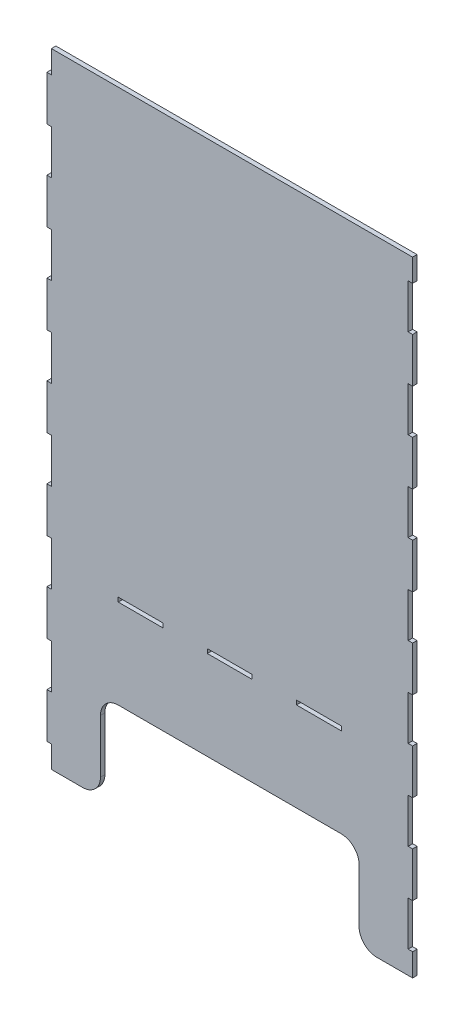
SolidWorks part; units mm, degrees
ref_plane "Ebene vorne" through (0, 0, 0) normal (0, 0, 1) x (1, 0, 0)
ref_plane "Ebene oben" through (0, 0, 0) normal (0, 1, 0) x (1, 0, 0)
ref_plane "Ebene rechts" through (0, 0, 0) normal (1, 0, 0) x (0, 0, -1)
sketch "Skizze1" plane through (0, 0, 0) normal (0, 0, 1) x (1, 0, 0)
  line L0 (0, 0) -> (0, 700)
  line L1 (0, 700) -> (410, 700)
  line L2 (410, 700) -> (410, 0)
  line L3 (410, 0) -> (370, 0)
  line L4 (0, 100) -> (410, 100) construction
  line L5 (60, 20) -> (60, 80)
  line L6 (350, 20) -> (350, 80)
  line L7 (330, 100) -> (80, 100)
  line L8 (40, 0) -> (0, 0)
  arc A0 (80, 100) -> (60, 80) centre (80, 80) ccw
  arc A1 (330, 100) -> (350, 80) centre (330, 80) cw
  arc A2 (40, 0) -> (60, 20) centre (40, 20) ccw
  arc A3 (370, 0) -> (350, 20) centre (370, 20) cw
  point P13 (60, 100)
  point P16 (350, 100)
  point P19 (60, 0)
  point P22 (350, 0)
  dimension "D4" = 20
  dimension "D5" = 20
  dimension "D8" = 20
  dimension "D9" = 20
  dimension "D1" = 700
  dimension "D2" = 410
  dimension "D3" = 100
  dimension "D6" = 60
  dimension "D7" = 60
extrude "Aufsatz-Linear austragen1" add sketch "Skizze1" along normal blind 5 contours L0 L1 L2 L3 A3 L6 A1 L7 A0 L5 A2 L8
sketch "Skizze2" plane through (0, 0, 5) normal (0, 0, 1) x (1, 0, 0)
  line L0 (0, 0) -> (0, 700) construction
  line L1 (79.95, 204.8) -> (130.25, 204.8)
  line L2 (79.95, 204.8) -> (79.95, 200)
  line L3 (79.95, 200) -> (130.25, 200)
  line L4 (130.25, 204.8) -> (130.25, 200)
  point P8 (13.0057, 298.352)
  dimension "D1" = 50.3
  dimension "D2" = 4.8
  dimension "D3" = 79.95
  dimension "D4" = 200
extrude "Schnitt-Linear austragen1" cut sketch "Skizze2" against normal blind 5
pattern_linear "Lineares Muster1" count 3 spacing 99.9 along (1, 0, 0) of "Schnitt-Linear austragen1"
sketch "Skizze3" plane through (0, 0, 5) normal (0, 0, 1) x (1, 0, 0)
  line L0 (0, 700) -> (410, 700) construction
  line L1 (-87.9124, 674.5) -> (5, 674.5)
  line L2 (-87.9124, 674.5) -> (-87.9124, 724.1)
  line L3 (-87.9124, 724.1) -> (5, 724.1)
  line L4 (5, 674.5) -> (5, 724.1)
  dimension "D1" = 49.6
  dimension "D2" = 5
  dimension "D3" = 24.1
extrude "Schnitt-Linear austragen2" cut sketch "Skizze3" against normal blind 5
pattern_linear "Lineares Muster2" count 8 spacing 99.9 along (0, -1, 0) of "Schnitt-Linear austragen2"
ref_plane "Ebene1" through (205, 0, 0) normal (1, 0, 0) x (0, 0, -1)
mirror "Spiegeln2" [suppressed] about plane through (205, 0, 0) normal (1, 0, 0)
sketch "Skizze5" [suppressed] plane through (0, 0, 5) normal (0, 0, 1) x (1, 0, 0)
  line L1 (5, 50.3) -> (-32.3107, 50.3)
  line L2 (5, 50.3) -> (5, -36.4204)
  line L3 (5, -36.4204) -> (-32.3107, -36.4204)
  line L4 (-32.3107, 50.3) -> (-32.3107, -36.4204)
extrude "Schnitt-Linear austragen3" [suppressed] cut sketch "Skizze5" against normal blind 5
sketch "Skizze4" plane through (0, 0, 5) normal (0, 0, 1) x (1, 0, 0)
  line L1 (405, 674.5) -> (491.468, 674.5)
  line L2 (405, 674.5) -> (405, 624.9)
  line L3 (405, 624.9) -> (491.468, 624.9)
  line L4 (491.468, 674.5) -> (491.468, 624.9)
  line L5 (410, 700) -> (410, 0) construction
  dimension "D1" = 49.6
  dimension "D2" = 5
  dimension "D3" = 25.5
extrude "Schnitt-Linear austragen4" cut sketch "Skizze4" against normal blind 5
pattern_linear "Lineares Muster3" count 7 spacing 99.9 along (0, -1, 0) of "Schnitt-Linear austragen4"
sketch "Skizze6" [suppressed] plane through (0, 0, 5) normal (0, 0, 1) x (1, 0, 0)
  line L14 (130.25, -5) -> (130.25, 0)
  line L15 (130.25, 0) -> (79.95, 0)
  line L16 (79.95, 0) -> (79.95, -5)
  line L17 (79.95, -5) -> (130.25, -5)
  line L18 (230.15, -5) -> (230.15, 0)
  line L19 (230.15, 0) -> (179.85, 0)
  line L20 (179.85, 0) -> (179.85, -5)
  line L21 (179.85, -5) -> (230.15, -5)
  line L22 (330.05, -5) -> (330.05, 0)
  line L23 (330.05, 0) -> (279.75, 0)
  line L24 (279.75, 0) -> (279.75, -5)
  line L25 (279.75, -5) -> (330.05, -5)
  line L26 (405, 0) -> (405, -5)
  line L27 (5, 0) -> (5, -5)
  point P16 (0, 0)
sketch "Skizze8" plane through (0, 0, 5) normal (0, 0, 1) x (1, 0, 0)
  line L0 (336.9108, 311.7971) -> (336.9108, 326.3757)
  line L1 (328.6083, 313.8519) -> (328.6083, 327.2541)
  line L2 (328.6083, 333.6697) -> (328.6083, 343.167)
  line L3 (336.9108, 332.9761) -> (336.9108, 342.6373)
  line L4 (327.3926, 291.1393) -> (324.9309, 261.8997)
  line L5 (336.9108, 292.9614) -> (336.9108, 262.1213)
  line L6 (361.3498, 305.4845) -> (370.8351, 305.9572)
  line L7 (340.5076, 297.1544) -> (354.5447, 297.1544)
  line L8 (319.162, 305.9572) -> (306.9363, 311.3902)
  line L9 (319.162, 298.8014) -> (305.6301, 298.0451)
  line L10 (301.0772, 313.9939) -> (292.4018, 317.8492)
  line L11 (299.1984, 297.6857) -> (289.6925, 297.1544)
  line L12 (361.0653, 297.1544) -> (370.6564, 297.1544)
  line L13 (341.558, 304.4982) -> (354.9423, 305.1652)
  line L14 (354.9423, 305.1652) -> (354.4332, 305.5514)
  line L15 (88.2286, 278.6972) -> (88.2286, 273.2138)
  line L16 (102.4933, 343.167) -> (102.4933, 259.9015) construction
  line L17 (116.7579, 273.2138) -> (116.7579, 278.6972)
  line L18 (116.7579, 288.6972) -> (116.7579, 273.2138)
  line L19 (77.4933, 288.6972) -> (78.2286, 288.6972)
  line L20 (126.7579, 288.6972) -> (127.4933, 288.6972)
  line L21 (119.7579, 273.2138) -> (119.7579, 278.6972)
  line L22 (126.7579, 285.6972) -> (127.4933, 285.6972)
  line L23 (77.4933, 285.6972) -> (78.2286, 285.6972)
  line L24 (85.2286, 278.6972) -> (85.2286, 273.2138)
  line L25 (126.7579, 273.2138) -> (126.7579, 278.6972)
  line L26 (126.7579, 282.6972) -> (127.4933, 282.6972)
  line L27 (122.7579, 273.2138) -> (122.7579, 278.6972)
  line L28 (82.2286, 278.6972) -> (82.2286, 273.2138)
  line L29 (77.4933, 282.6972) -> (78.2286, 282.6972)
  line L30 (126.7579, 278.6972) -> (127.4933, 278.6972)
  line L31 (102.4933, 290.7717) -> (102.4933, 229.2493) construction
  line L32 (102.4933, 229.2493) -> (102.4933, 290.7717)
  line L33 (77.4933, 278.6972) -> (78.2286, 278.6972)
  line L34 (78.2286, 278.6972) -> (78.2286, 273.2138)
  line L36 (129.7579, 273.2138) -> (129.7579, 275.8402)
  line L37 (129.7579, 275.8402) -> (129.7579, 275.8402)
  line L38 (75.2286, 275.8402) -> (75.2286, 275.8402)
  line L39 (75.2286, 275.8402) -> (75.2286, 273.2138)
  arc A0 (328.6083, 343.167) -> (292.4018, 317.8492) centre (330.1744, 302.3793) ccw
  arc A1 (328.6083, 333.6697) -> (301.0772, 313.9939) centre (330.1744, 302.3793) ccw
  arc A2 (328.6083, 327.2541) -> (306.9363, 311.3902) centre (330.1744, 302.3793) ccw
  arc A3 (328.6083, 313.8519) -> (319.162, 305.9572) centre (330.1744, 302.3793) ccw
  arc A4 (319.162, 298.8014) -> (340.5076, 297.1544) centre (330.1744, 302.3793) ccw
  arc A5 (305.6301, 298.0451) -> (354.5447, 297.1544) centre (330.1744, 302.3793) ccw
  arc A6 (299.1984, 297.6857) -> (361.0653, 297.1544) centre (330.1744, 302.3793) ccw
  arc A7 (289.6925, 297.1544) -> (370.6564, 297.1544) centre (330.1744, 302.3793) ccw
  arc A8 (341.558, 304.4982) -> (336.9108, 311.7971) centre (330.1744, 302.3793) ccw
  arc A9 (354.9423, 305.1652) -> (336.9108, 326.3757) centre (330.1744, 302.3793) ccw
  arc A10 (361.3498, 305.4845) -> (336.9108, 332.9761) centre (330.1744, 302.3793) ccw
  arc A11 (370.8351, 305.9572) -> (336.9108, 342.6373) centre (330.1744, 302.3793) ccw
  arc A12 (72.5271, 294.2784) -> (132.4594, 294.2784) centre (102.4933, 290.7717) cw
  arc A13 (132.4594, 294.2784) -> (127.4933, 288.6972) centre (127.4933, 293.6972) cw
  arc A14 (72.5271, 294.2784) -> (77.4933, 288.6972) centre (77.4933, 293.6972) ccw
  arc A15 (78.2286, 288.6972) -> (88.2286, 278.6972) centre (78.2286, 278.6972) cw
  arc A16 (126.7579, 288.6972) -> (116.7579, 278.6972) centre (126.7579, 278.6972) ccw
  arc A17 (88.2286, 273.2138) -> (116.7579, 273.2138) centre (102.4933, 273.2138) ccw
  arc A18 (126.7579, 285.6972) -> (119.7579, 278.6972) centre (126.7579, 278.6972) ccw
  arc A19 (135.439, 294.627) -> (127.4933, 285.6972) centre (127.4933, 293.6972) cw
  arc A20 (69.5475, 294.627) -> (135.439, 294.627) centre (102.4933, 290.7717) cw
  arc A21 (69.5475, 294.627) -> (77.4933, 285.6972) centre (77.4933, 293.6972) ccw
  arc A22 (78.2286, 285.6972) -> (85.2286, 278.6972) centre (78.2286, 278.6972) cw
  arc A23 (85.2286, 273.2138) -> (119.7579, 273.2138) centre (102.4933, 273.2138) ccw
  arc A24 (66.5678, 294.9757) -> (138.4187, 294.9757) centre (102.4933, 290.7717) cw
  arc A25 (138.4187, 294.9757) -> (127.4933, 282.6972) centre (127.4933, 293.6972) cw
  arc A26 (126.7579, 282.6972) -> (122.7579, 278.6972) centre (126.7579, 278.6972) ccw
  arc A27 (82.2286, 273.2138) -> (122.7579, 273.2138) centre (102.4933, 273.2138) ccw
  arc A28 (78.2286, 282.6972) -> (82.2286, 278.6972) centre (78.2286, 278.6972) cw
  arc A29 (66.5678, 294.9757) -> (77.4933, 282.6972) centre (77.4933, 293.6972) ccw
  arc A30 (126.7579, 278.6972) -> (126.7579, 278.6972) centre (126.7579, 278.6972) ccw
  arc A31 (142.3916, 295.4406) -> (127.4933, 278.6972) centre (127.4933, 293.6972) cw
  arc A32 (62.5949, 295.4406) -> (142.3916, 295.4406) centre (102.4933, 290.7717) cw
  arc A33 (62.5949, 295.4406) -> (77.4933, 278.6972) centre (77.4933, 293.6972) ccw
  arc A34 (78.2286, 278.6972) -> (78.2286, 278.6972) centre (78.2286, 278.6972) cw
  arc A35 (78.2286, 273.2138) -> (126.7579, 273.2138) centre (102.4933, 273.2138) ccw
  arc A36 (129.7579, 275.8402) -> (129.7579, 275.8402) centre (129.7579, 275.8402) ccw
  arc A37 (145.3713, 295.7893) -> (129.7579, 275.8402) centre (127.4933, 293.6972) cw
  arc A38 (59.6153, 295.7893) -> (145.3713, 295.7893) centre (102.4933, 290.7717) cw
  arc A39 (59.6153, 295.7893) -> (75.2286, 275.8402) centre (77.4933, 293.6972) ccw
  arc A40 (75.2286, 275.8402) -> (75.2286, 275.8402) centre (75.2286, 275.8402) cw
  arc A41 (75.2286, 273.2138) -> (129.7579, 273.2138) centre (102.4933, 273.2138) ccw
  arc A42 (78.2286, 288.6972) -> (88.2286, 278.6972) centre (78.2286, 278.6972) cw construction
  point P29 (0, 0)
  dimension "D1" = 5
  dimension "D2" = 10
  dimension "D3" = 10
  dimension "D4" = 25
  dimension "D5" = 25
  dimension "D6" = 10
  dimension "D7" = 3
  dimension "D8" = 3
equation "\"D1@Ebene1\"=410/2"
